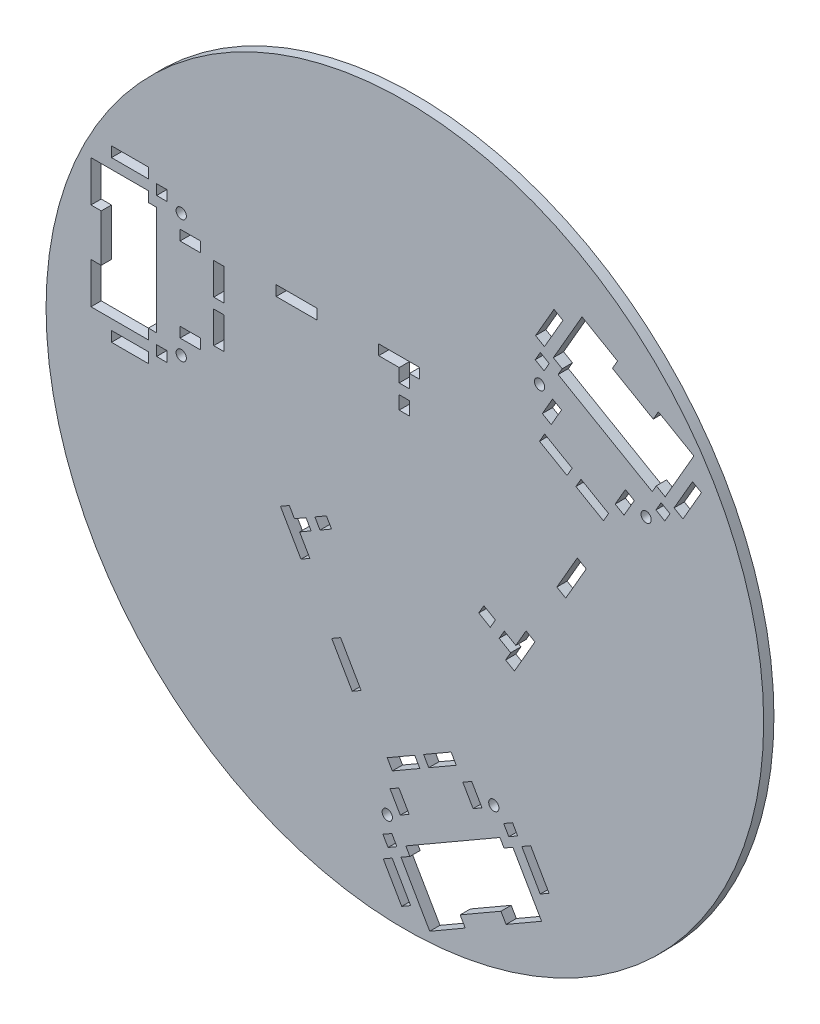
SolidWorks part; units mm, degrees
ref_plane "Plan de face" through (0, 0, 0) normal (0, 0, 1) x (1, 0, 0)
ref_plane "Plan de dessus" through (0, 0, 0) normal (0, 1, 0) x (1, 0, 0)
ref_plane "Plan de droite" through (0, 0, 0) normal (1, 0, 0) x (0, 0, -1)
sketch "Esquisse1" plane through (0, 0, 0) normal (0, 0, 1) x (1, 0, 0)
  circle A0 centre (148.0804, -12.1102) radius 175
extrude "Boss.-Extru.1" add sketch "Esquisse1" along normal blind 5
sketch "Esquisse2" plane through (0, 0, 0) normal (0, 0, -1) x (-1, 0, 0)
  line L0 (-155.3118, 53.7774) -> (-135.3118, 53.7774)
  line L1 (-150.3118, 37.2774) -> (-145.3118, 37.2774)
  line L2 (-150.3118, 37.2774) -> (-150.3118, 30.7774)
  line L3 (-150.3118, 30.7774) -> (-145.3118, 30.7774)
  line L4 (-145.3118, 37.2774) -> (-145.3118, 30.7774)
  line L5 (-105.3118, 53.7774) -> (-85.3118, 53.7774)
  line L6 (-105.3118, 53.7774) -> (-105.3118, 48.7774)
  line L7 (-105.3118, 48.7774) -> (-85.3118, 48.7774)
  line L8 (-85.3118, 53.7774) -> (-85.3118, 48.7774)
  line L9 (-59.86, 48.7774) -> (-54.86, 48.7774)
  line L10 (-59.86, 48.7774) -> (-59.86, 33.2774)
  line L11 (-59.86, 33.2774) -> (-54.86, 33.2774)
  line L12 (-54.86, 48.7774) -> (-54.86, 33.2774)
  line L13 (-59.86, 28.2774) -> (-54.86, 28.2774)
  line L14 (-59.86, 28.2774) -> (-59.86, 12.7774)
  line L15 (-59.86, 12.7774) -> (-54.86, 12.7774)
  line L16 (-54.86, 28.2774) -> (-54.86, 12.7774)
  line L17 (-48.43, 12.7774) -> (-38.43, 12.7774)
  line L18 (-48.43, 12.7774) -> (-48.43, 7.7774)
  line L19 (-48.43, 7.7774) -> (-38.43, 7.7774)
  line L20 (-38.43, 12.7774) -> (-38.43, 7.7774)
  line L21 (-32, -0.7226) -> (-27, -0.7226)
  line L22 (-32, -0.7226) -> (-32, -5.7226)
  line L23 (-32, -5.7226) -> (-27, -5.7226)
  line L24 (-27, -0.7226) -> (-27, -5.7226)
  line L25 (-23, -5.7226) -> (-5, -5.7226)
  line L26 (-23, -5.7226) -> (-23, -10.7226)
  line L27 (-23, -10.7226) -> (-5, -10.7226)
  line L28 (-5, -5.7226) -> (-5, -10.7226)
  line L29 (0, -0.7226) -> (5, -0.7226)
  line L30 (0, -0.7226) -> (0, 19.2774)
  line L31 (0, 19.2774) -> (5, 19.2774)
  line L32 (5, -0.7226) -> (5, 19.2774)
  line L33 (0, 42.2774) -> (5, 42.2774)
  line L34 (0, 42.2774) -> (0, 62.2774)
  line L35 (0, 62.2774) -> (5, 62.2774)
  line L36 (5, 42.2774) -> (5, 62.2774)
  line L37 (-23, 67.2774) -> (-5, 67.2774)
  line L38 (-23, 67.2774) -> (-23, 72.2774)
  line L39 (-23, 72.2774) -> (-5, 72.2774)
  line L40 (-5, 67.2774) -> (-5, 72.2774)
  line L41 (-27, 67.2774) -> (-32, 67.2774)
  line L42 (-27, 67.2774) -> (-27, 62.2774)
  line L43 (-27, 62.2774) -> (-32, 62.2774)
  line L44 (-32, 67.2774) -> (-32, 62.2774)
  line L45 (-38.43, 53.7774) -> (-48.43, 53.7774)
  line L46 (-38.43, 53.7774) -> (-38.43, 48.7774)
  line L47 (-38.43, 48.7774) -> (-48.43, 48.7774)
  line L48 (-48.43, 53.7774) -> (-48.43, 48.7774)
  line L49 (-135.3118, 53.7774) -> (-135.3118, 48.7774)
  line L50 (-135.3118, 48.7774) -> (-145.3118, 48.7774)
  line L51 (-135.3118, 48.7774) -> (-155.3118, 48.7774) construction
  line L52 (-145.3118, 48.7774) -> (-145.3118, 42.2774)
  line L53 (-145.3118, 42.2774) -> (-150.3118, 42.2774)
  line L54 (-150.3118, 42.2774) -> (-150.3118, 48.7774)
  line L55 (-150.3118, 48.7774) -> (-155.3118, 48.7774)
  line L56 (-155.3118, 48.7774) -> (-155.3118, 53.7774)
  line L57 (-87.4044, -38.7914) -> (-97.4044, -56.1119)
  line L58 (-104.1938, -34.8716) -> (-106.6938, -39.2017)
  line L59 (-104.1938, -34.8716) -> (-109.823, -31.6216)
  line L60 (-109.823, -31.6216) -> (-112.323, -35.9517)
  line L61 (-106.6938, -39.2017) -> (-112.323, -35.9517)
  line L62 (-112.4044, -82.0927) -> (-122.4044, -99.4132)
  line L63 (-112.4044, -82.0927) -> (-116.7345, -79.5927)
  line L64 (-116.7345, -79.5927) -> (-126.7345, -96.9132)
  line L65 (-122.4044, -99.4132) -> (-126.7345, -96.9132)
  line L66 (-139.4604, -118.9551) -> (-141.9604, -123.2852)
  line L67 (-139.4604, -118.9551) -> (-152.8838, -111.2051)
  line L68 (-152.8838, -111.2051) -> (-155.3838, -115.5352)
  line L69 (-141.9604, -123.2852) -> (-155.3838, -115.5352)
  line L70 (-157.2139, -108.7051) -> (-159.7139, -113.0352)
  line L71 (-157.2139, -108.7051) -> (-170.6373, -100.9551)
  line L72 (-170.6373, -100.9551) -> (-173.1373, -105.2852)
  line L73 (-159.7139, -113.0352) -> (-173.1373, -105.2852)
  line L74 (-176.3523, -110.8538) -> (-181.3523, -119.514)
  line L75 (-176.3523, -110.8538) -> (-180.6825, -108.3538)
  line L76 (-180.6825, -108.3538) -> (-185.6825, -117.014)
  line L77 (-181.3523, -119.514) -> (-185.6825, -117.014)
  line L78 (-196.2587, -118.3326) -> (-198.7587, -122.6627)
  line L79 (-196.2587, -118.3326) -> (-200.5888, -115.8326)
  line L80 (-200.5888, -115.8326) -> (-203.0888, -120.1627)
  line L81 (-198.7587, -122.6627) -> (-203.0888, -120.1627)
  line L82 (-205.0888, -123.6268) -> (-214.0888, -139.2153)
  line L83 (-205.0888, -123.6268) -> (-209.4189, -121.1268)
  line L84 (-209.4189, -121.1268) -> (-218.4189, -136.7153)
  line L85 (-214.0888, -139.2153) -> (-218.4189, -136.7153)
  line L86 (-212.2587, -146.0454) -> (-214.7587, -150.3755)
  line L87 (-212.2587, -146.0454) -> (-194.9382, -156.0454)
  line L88 (-194.9382, -156.0454) -> (-197.4382, -160.3755)
  line L89 (-214.7587, -150.3755) -> (-197.4382, -160.3755)
  line L90 (-175.0196, -167.5454) -> (-177.5196, -171.8755)
  line L91 (-175.0196, -167.5454) -> (-157.6991, -177.5454)
  line L92 (-157.6991, -177.5454) -> (-160.1991, -181.8755)
  line L93 (-177.5196, -171.8755) -> (-160.1991, -181.8755)
  line L94 (-141.869, -160.1268) -> (-150.869, -175.7153)
  line L95 (-141.869, -160.1268) -> (-137.5388, -162.6268)
  line L96 (-137.5388, -162.6268) -> (-146.5388, -178.2153)
  line L97 (-150.869, -175.7153) -> (-146.5388, -178.2153)
  line L98 (-139.869, -156.6627) -> (-137.369, -152.3326)
  line L99 (-139.869, -156.6627) -> (-144.1991, -154.1627)
  line L100 (-144.1991, -154.1627) -> (-141.6991, -149.8326)
  line L101 (-137.369, -152.3326) -> (-141.6991, -149.8326)
  line L102 (-145.8453, -140.014) -> (-140.8453, -131.3538)
  line L103 (-145.8453, -140.014) -> (-150.1754, -137.514)
  line L104 (-150.1754, -137.514) -> (-145.1754, -128.8538)
  line L105 (-140.8453, -131.3538) -> (-145.1754, -128.8538)
  line L106 (-97.4044, -56.1119) -> (-101.7345, -53.6119)
  line L107 (-101.7345, -53.6119) -> (-96.7345, -44.9517)
  line L108 (-96.7345, -44.9517) -> (-102.3637, -41.7017)
  line L109 (-102.3637, -41.7017) -> (-99.8637, -37.3716)
  line L110 (-99.8637, -37.3716) -> (-94.2345, -40.6216)
  line L111 (-94.2345, -40.6216) -> (-91.7345, -36.2914)
  line L112 (-91.7345, -36.2914) -> (-87.4044, -38.7914)
  line L113 (-201.5251, -51.3165) -> (-211.5251, -33.996)
  line L114 (-189.7357, -38.7364) -> (-192.2357, -34.4063)
  line L115 (-189.7357, -38.7364) -> (-184.1065, -35.4864)
  line L116 (-184.1065, -35.4864) -> (-186.6065, -31.1563)
  line L117 (-192.2357, -34.4063) -> (-186.6065, -31.1563)
  line L118 (-226.5251, -8.0153) -> (-236.5251, 9.3053)
  line L119 (-226.5251, -8.0153) -> (-222.195, -5.5153)
  line L120 (-222.195, -5.5153) -> (-232.195, 11.8053)
  line L121 (-236.5251, 9.3053) -> (-232.195, 11.8053)
  line L122 (-244.9209, 33.8472) -> (-247.4209, 38.1773)
  line L123 (-244.9209, 33.8472) -> (-231.4975, 41.5972)
  line L124 (-231.4975, 41.5972) -> (-233.9975, 45.9273)
  line L125 (-247.4209, 38.1773) -> (-233.9975, 45.9273)
  line L126 (-227.1673, 44.0972) -> (-229.6673, 48.4273)
  line L127 (-227.1673, 44.0972) -> (-213.7439, 51.8472)
  line L128 (-213.7439, 51.8472) -> (-216.2439, 56.1773)
  line L129 (-229.6673, 48.4273) -> (-216.2439, 56.1773)
  line L130 (-219.4589, 61.7458) -> (-224.4589, 70.4061)
  line L131 (-219.4589, 61.7458) -> (-215.1288, 64.2458)
  line L132 (-215.1288, 64.2458) -> (-220.1288, 72.9061)
  line L133 (-224.4589, 70.4061) -> (-220.1288, 72.9061)
  line L134 (-215.9826, 82.7246) -> (-218.4826, 87.0547)
  line L135 (-215.9826, 82.7246) -> (-211.6525, 85.2246)
  line L136 (-211.6525, 85.2246) -> (-214.1525, 89.5547)
  line L137 (-218.4826, 87.0547) -> (-214.1525, 89.5547)
  line L138 (-216.1525, 93.0188) -> (-225.1525, 108.6073)
  line L139 (-216.1525, 93.0188) -> (-211.8223, 95.5188)
  line L140 (-211.8223, 95.5188) -> (-220.8223, 111.1073)
  line L141 (-225.1525, 108.6073) -> (-220.8223, 111.1073)
  line L142 (-231.9826, 110.4374) -> (-234.4826, 114.7676)
  line L143 (-231.9826, 110.4374) -> (-249.3031, 100.4374)
  line L144 (-249.3031, 100.4374) -> (-251.8031, 104.7676)
  line L145 (-234.4826, 114.7676) -> (-251.8031, 104.7676)
  line L146 (-269.2217, 88.9374) -> (-271.7217, 93.2676)
  line L147 (-269.2217, 88.9374) -> (-286.5422, 78.9374)
  line L148 (-286.5422, 78.9374) -> (-289.0422, 83.2676)
  line L149 (-271.7217, 93.2676) -> (-289.0422, 83.2676)
  line L150 (-279.3723, 56.5188) -> (-288.3723, 72.1073)
  line L151 (-279.3723, 56.5188) -> (-283.7025, 54.0188)
  line L152 (-283.7025, 54.0188) -> (-292.7025, 69.6073)
  line L153 (-288.3723, 72.1073) -> (-292.7025, 69.6073)
  line L154 (-277.3723, 53.0547) -> (-274.8723, 48.7246)
  line L155 (-277.3723, 53.0547) -> (-273.0422, 55.5547)
  line L156 (-273.0422, 55.5547) -> (-270.5422, 51.2246)
  line L157 (-274.8723, 48.7246) -> (-270.5422, 51.2246)
  line L158 (-259.966, 49.9061) -> (-254.966, 41.2458)
  line L159 (-259.966, 49.9061) -> (-255.6359, 52.4061)
  line L160 (-255.6359, 52.4061) -> (-250.6359, 43.7458)
  line L161 (-254.966, 41.2458) -> (-250.6359, 43.7458)
  line L162 (-211.5251, -33.996) -> (-207.195, -31.496)
  line L163 (-207.195, -31.496) -> (-202.195, -40.1563)
  line L164 (-202.195, -40.1563) -> (-196.5658, -36.9063)
  line L165 (-196.5658, -36.9063) -> (-194.0658, -41.2364)
  line L166 (-194.0658, -41.2364) -> (-199.695, -44.4864)
  line L167 (-199.695, -44.4864) -> (-197.195, -48.8165)
  line L168 (-197.195, -48.8165) -> (-201.5251, -51.3165)
  point P204 (-148.0804, -12.1102)
  dimension "D1" = 3
extrude "Enlèv. mat.-Extru.1" cut sketch "Esquisse2" against normal blind 5
sketch "Esquisse3" plane through (0, 0, 0) normal (0, 0, -1) x (-1, 0, 0)
  line L0 (-59.86, 33.2774) -> (-59.86, 28.2774) construction
  line L1 (-59.86, 30.7774) -> (32.4397, 30.7774) construction
  line L2 (0, -0.7226) -> (-23, -0.7226)
  line L3 (-23, -0.7226) -> (-23, 4.2774)
  line L4 (-23, 4.2774) -> (-27, 4.2774)
  line L5 (-23, 57.2774) -> (-27, 57.2774)
  line L6 (-23, 62.2774) -> (-23, 57.2774)
  line L7 (0, 62.2774) -> (-23, 62.2774)
  line L8 (-27, 57.2774) -> (-27, 4.2774)
  line L9 (0, -0.7226) -> (0, 62.2774)
  line L10 (-212.2587, -146.0454) -> (-200.7587, -126.1268)
  line L11 (-200.7587, -126.1268) -> (-196.4286, -128.6268)
  line L12 (-196.4286, -128.6268) -> (-194.4286, -125.1627)
  line L13 (-150.5292, -155.1268) -> (-148.5292, -151.6627)
  line L14 (-146.1991, -157.6268) -> (-150.5292, -155.1268)
  line L15 (-157.6991, -177.5454) -> (-146.1991, -157.6268)
  line L16 (-148.5292, -151.6627) -> (-194.4286, -125.1627)
  line L17 (-212.2587, -146.0454) -> (-157.6991, -177.5454)
  line L18 (-152.8838, -111.2051) -> (-157.2139, -108.7051) construction
  line L19 (-155.0489, -109.9551) -> (-201.1987, -189.889) construction
  line L20 (-231.9826, 110.4374) -> (-220.4826, 90.5188)
  line L21 (-220.4826, 90.5188) -> (-224.8127, 88.0188)
  line L22 (-224.8127, 88.0188) -> (-222.8127, 84.5547)
  line L23 (-270.7121, 61.5188) -> (-268.7121, 58.0547)
  line L24 (-275.0422, 59.0188) -> (-270.7121, 61.5188)
  line L25 (-286.5422, 78.9374) -> (-275.0422, 59.0188)
  line L26 (-268.7121, 58.0547) -> (-222.8127, 84.5547)
  line L27 (-231.9826, 110.4374) -> (-286.5422, 78.9374)
  line L28 (-231.4975, 41.5972) -> (-227.1673, 44.0972) construction
  line L29 (-229.3324, 42.8472) -> (-275.4822, 122.781) construction
  point P42 (-148.0804, -12.1102)
  dimension "D1" = 5
  dimension "D2" = 4
  dimension "D3" = 23
  dimension "D4" = 3
extrude "Enlèv. mat.-Extru.2" cut sketch "Esquisse3" against normal blind 5
sketch "Esquisse4" plane through (0, 0, 0) normal (0, 0, -1) x (-1, 0, 0)
  line L0 (-32, 67.2774) -> (-32, 62.2774) construction
  line L1 (-38.43, 53.7774) -> (-48.43, 53.7774) construction
  line L2 (-27, 30.7774) -> (-93.5454, 30.7774) construction
  line L3 (-27, 57.2774) -> (-27, 4.2774) construction
  line L4 (-171.4789, -138.4127) -> (-138.2062, -80.7827) construction
  line L5 (-245.7624, 71.3047) -> (-212.4897, 13.6748) construction
  circle A0 centre (-39, 60.7774) radius 2.5
  circle A1 centre (-39, 0.7774) radius 2.5
  circle A2 centre (-139.4981, -143.0204) radius 2.5
  circle A3 centre (-191.4596, -113.0204) radius 2.5
  circle A4 centre (-265.7432, 45.9124) radius 2.5
  circle A5 centre (-213.7816, 75.9124) radius 2.5
  point P27 (-148.0804, -12.1102)
  dimension "D1" = 7
  dimension "D2" = 7
  dimension "D3" = 3
extrude "Enlèv. mat.-Extru.3" cut sketch "Esquisse4" against normal blind 5
